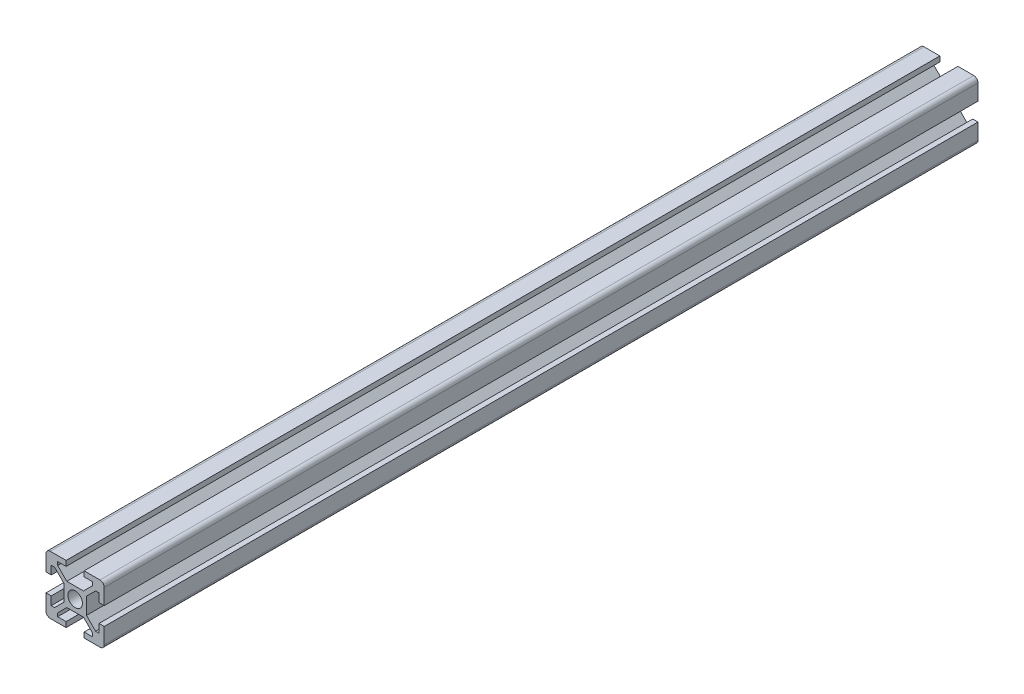
SolidWorks part; units mm, degrees
ref_plane "Front Plane" through (0, 0, 0) normal (0, 0, 1) x (1, 0, 0)
ref_plane "Top Plane" through (0, 0, 0) normal (0, 1, 0) x (1, 0, 0)
ref_plane "Right Plane" through (0, 0, 0) normal (1, 0, 0) x (0, 0, -1)
sketch "Sketch1" plane through (0, 0, 0) normal (0, 0, 1) x (1, 0, 0)
  line L0 (2.8606, 3.9) -> (6, 7.0394)
  line L5 (0, 3.9) -> (2.8606, 3.9)
  line L8 (3.9, 2.8606) -> (3.9, 0)
  line L9 (3.9, 0) -> (3.9, -2.8606)
  line L10 (3.9, -2.8606) -> (7.0394, -6)
  line L11 (6, 7.0394) -> (6, 8.2)
  line L12 (6, 8.2) -> (3.1, 8.2)
  line L13 (3.1, 8.2) -> (3.1, 10)
  line L14 (3.1, 10) -> (10, 10)
  line L15 (10, 10) -> (10, 3.1)
  line L16 (10, 3.1) -> (8.2, 3.1)
  line L17 (8.2, 3.1) -> (8.2, 6)
  line L18 (8.2, 6) -> (7.0394, 6)
  line L19 (7.0394, 6) -> (3.9, 2.8606)
  line L22 (7.0394, -6) -> (8.2, -6)
  line L23 (8.2, -6) -> (8.2, -3.1)
  line L24 (8.2, -3.1) -> (10, -3.1)
  line L25 (10, -3.1) -> (10, -10)
  line L26 (10, -10) -> (3.1, -10)
  line L27 (3.1, -10) -> (3.1, -8.2)
  line L28 (3.1, -8.2) -> (6, -8.2)
  line L29 (6, -8.2) -> (6, -7.0394)
  line L30 (6, -7.0394) -> (2.8606, -3.9)
  line L31 (2.8606, -3.9) -> (0, -3.9)
  line L32 (0, -3.9) -> (-2.8606, -3.9)
  line L33 (-2.8606, -3.9) -> (-6, -7.0394)
  line L34 (-6, -7.0394) -> (-6, -8.2)
  line L35 (-6, -8.2) -> (-3.1, -8.2)
  line L36 (-3.1, -8.2) -> (-3.1, -10)
  line L37 (-3.1, -10) -> (-10, -10)
  line L38 (-10, -10) -> (-10, -3.1)
  line L39 (-10, -3.1) -> (-8.2, -3.1)
  line L40 (-8.2, -3.1) -> (-8.2, -6)
  line L41 (-8.2, -6) -> (-7.0394, -6)
  line L42 (-7.0394, -6) -> (-3.9, -2.8606)
  line L43 (-3.9, -2.8606) -> (-3.9, 0)
  line L44 (-3.9, 0) -> (-3.9, 2.8606)
  line L45 (-3.9, 2.8606) -> (-7.0394, 6)
  line L46 (-7.0394, 6) -> (-8.2, 6)
  line L47 (-8.2, 6) -> (-8.2, 3.1)
  line L48 (-8.2, 3.1) -> (-10, 3.1)
  line L49 (-10, 3.1) -> (-10, 10)
  line L50 (-10, 10) -> (-3.1, 10)
  line L51 (-3.1, 10) -> (-3.1, 8.2)
  line L52 (-3.1, 8.2) -> (-6, 8.2)
  line L53 (-6, 8.2) -> (-6, 7.0394)
  line L54 (-6, 7.0394) -> (-2.8606, 3.9)
  line L55 (-2.8606, 3.9) -> (0, 3.9)
  circle A0 centre (0, 0) radius 2.5
  point P0 (0, 0)
  dimension "D9" = 5
  dimension "D1" = 45
  dimension "D2" = 10
  dimension "D3" = 6.1
  dimension "D4" = 3.1
  dimension "D5" = 1.47
  dimension "D6" = 4.3
  dimension "D7" = 6
  dimension "D8" = 4
extrude "Boss-Extrude1" add sketch "Sketch1" along normal blind 300
fillet "Fillet1" radius 1.47 4 edges at (-10, -10, 150) (-10, 10, 150) (10, -10, 150) (10, 10, 150)
sketch "Sketch2" plane through (3.9, 0, 0) normal (1, 0, 0) x (0, 0, -1)
  circle A0 centre (-150, 0) radius 1.5
  dimension "D1" = 3
  dimension "D2" = 150
extrude "Cut-Extrude1" cut sketch "Sketch2" against normal through all
sketch "Sketch3" plane through (3.9, 0, 0) normal (1, 0, 0) x (0, 0, -1)
  line L0 (0, -2.8606) -> (0, 2.8606) construction
  circle A0 centre (-77.5, 0) radius 1.5
  point P2 (0, 0)
  dimension "D1" = 3
  dimension "D2" = 77.5
extrude "Cut-Extrude2" cut sketch "Sketch3" against normal through all contours A0
sketch "Sketch4" plane through (0, 3.9, 0) normal (0, 1, 0) x (1, 0, 0)
  line L0 (2.8606, -300) -> (-2.8606, -300) construction
  circle A0 centre (0, -50) radius 1.5
  circle A1 centre (0, -250) radius 1.5
  dimension "D1" = 3
  dimension "D3" = 3
  dimension "D2" = 50
  dimension "D4" = 50
extrude "Cut-Extrude3" cut sketch "Sketch4" against normal through all
